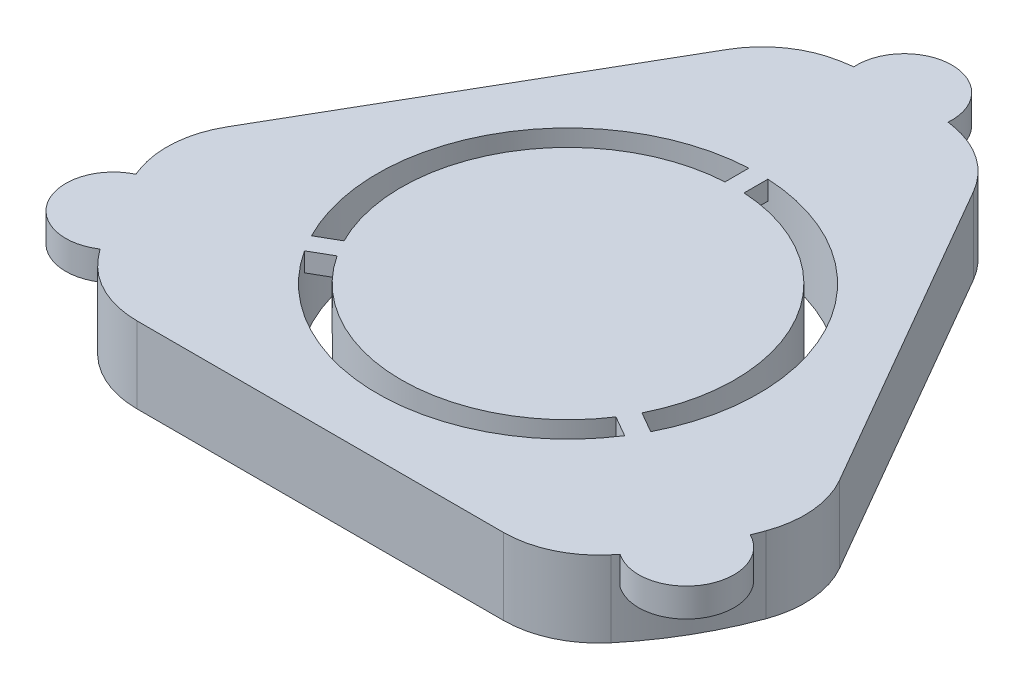
SolidWorks part; units mm, degrees
ref_plane "Спереди" through (0, 0, 0) normal (0, 0, 1) x (1, 0, 0)
ref_plane "Сверху" through (0, 0, 0) normal (0, 1, 0) x (1, 0, 0)
ref_plane "Справа" through (0, 0, 0) normal (1, 0, 0) x (0, 0, -1)
sketch "Sketch1" plane through (0, 0, 0) normal (0, 1, 0) x (1, 0, 0)
  circle A0 centre (0, 0) radius 20
  dimension "D1" = 40
extrude "Boss-Extrude1" add sketch "Sketch1" along normal blind 3.5
sketch "Sketch2" plane through (0, 0, 0) normal (0, 1, 0) x (1, 0, 0)
  circle A0 centre (0, 0) radius 35
  circle A1 centre (0, 0) radius 20
  circle A2 centre (0, 0) radius 29 construction
  circle A3 centre (0, 29) radius 2.8
  circle A4 centre (25.1147, -14.5) radius 2.8
  circle A5 centre (-25.1147, -14.5) radius 2.8
  point P16 (0, 0)
  dimension "D2" = 58
  dimension "D3" = 40
  dimension "D4" = 70
  dimension "D1" = 3
extrude "Boss-Extrude2" add sketch "Sketch2" along normal blind 8
sketch "Sketch4" plane through (0, 0, 0) normal (0, -1, 0) x (1, 0, 0)
  circle A0 centre (-25.1147, 14.5) radius 2.9
  circle A1 centre (25.1147, 14.5) radius 2.9
  circle A2 centre (0, -29) radius 2.9
  point P9 (0, 0)
  dimension "D1" = 3
extrude "Boss-Extrude3" add sketch "Sketch4" along normal blind 2 and the other way up to surface (8 mm away) other way up to face at (25.1147, 8, 17.3)
sketch "Sketch5" plane through (0, 8, 0) normal (0, 1, 0) x (1, 0, 0)
  circle A0 centre (-30.4536, -17.2504) radius 5
  circle A1 centre (0, 0) radius 35 construction
  circle A2 centre (0.2875, 34.9988) radius 5
  circle A3 centre (30.1661, -17.7484) radius 5
  point P10 (0, 0)
  dimension "D1" = 3
extrude "Boss-Extrude4" add sketch "Sketch5" against normal blind 3
sketch "Sketch3" plane through (0, 3.5, 0) normal (0, 1, 0) x (1, 0, 0)
  circle A0 centre (0, 0) radius 20
  dimension "D1" = 40
extrude "Cut-Extrude1" cut sketch "Sketch3" against normal blind 10
sketch "Sketch9" plane through (0, 8, 0) normal (0, 1, 0) x (1, 0, 0)
  circle A0 centre (0, 0) radius 17.5
  dimension "D1" = 35
extrude "Boss-Extrude5" add sketch "Sketch9" against normal blind 3.5 separate body
sketch "Sketch10" plane through (0, 4.5, 0) normal (0, -1, 0) x (-1, 0, 0)
  circle A0 centre (0, 0) radius 17.5
  circle A1 centre (0, 0) radius 16.5
  circle A2 centre (0, 0) radius 17.5 construction
  dimension "D1" = 1
extrude "Boss-Extrude6" add sketch "Sketch10" along normal up to surface (4.5 mm away) up to face at (0, 0, 20)
sketch "Sketch11" plane through (0, 8, 0) normal (0, 1, 0) x (1, 0, 0)
  line L0 (19.9463, -10.3613) -> (14.2313, -7.0617)
  line L1 (-1, 22.4546) -> (1, 22.4546)
  line L2 (-1, 22.4546) -> (-1, 15.8555)
  line L3 (-1, 15.8555) -> (1, 15.8555)
  line L4 (1, 22.4546) -> (1, 15.8555)
  line L5 (-1, 22.4546) -> (1, 15.8555) construction
  line L6 (-1, 15.8555) -> (1, 22.4546) construction
  line L7 (19.9463, -10.3613) -> (18.9463, -12.0933)
  line L8 (18.9463, -12.0933) -> (13.2313, -8.7938)
  line L9 (14.2313, -7.0617) -> (13.2313, -8.7938)
  line L10 (-18.9463, -12.0933) -> (-13.2313, -8.7938)
  line L11 (-18.9463, -12.0933) -> (-19.9463, -10.3613)
  line L12 (-19.9463, -10.3613) -> (-14.2313, -7.0617)
  line L13 (-13.2313, -8.7938) -> (-14.2313, -7.0617)
  point P0 (0, 19.1551)
  point P15 (0, 0)
  dimension "D1" = 3
extrude "Boss-Extrude7" add sketch "Sketch11" against normal blind 2
sketch "Sketch12" plane through (0, 8, 0) normal (0, 1, 0) x (1, 0, 0)
  line L1 (0, 52) -> (-45.0333, -26)
  line L2 (-45.0333, -26) -> (45.0333, -26)
  line L3 (45.0333, -26) -> (0, 52)
  circle A0 centre (0, 0) radius 26 construction
  circle A1 centre (0, 0) radius 72.1359
extrude "Cut-Extrude2" cut sketch "Sketch12" against normal blind 22
fillet "Fillet1" radius 10 6 edges at (-23.4307, 4, 26) (23.4307, 4, 26) (-10.8013, 4, -33.2916) (-34.232, 4, 7.2916) (34.232, 4, 7.2916) (10.8013, 4, -33.2916)
